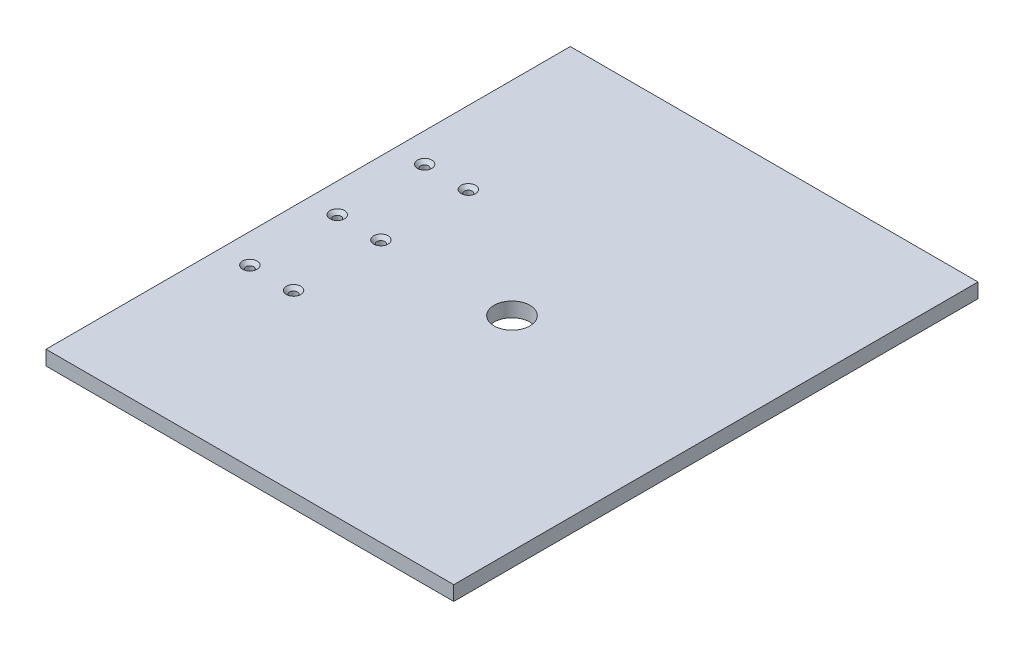
SolidWorks part; units mm, degrees
ref_plane "Front" through (0, 0, 0) normal (0, 0, 1) x (1, 0, 0)
ref_plane "Top" through (0, 0, 0) normal (0, 1, 0) x (1, 0, 0)
ref_plane "Right" through (0, 0, 0) normal (1, 0, 0) x (0, 0, -1)
sketch "Sketch1" plane through (0, 0, 0) normal (0, 1, 0) x (1, 0, 0)
  line L1 (0, -114.3) -> (177.8, -114.3)
  line L2 (0, -114.3) -> (0, 114.3)
  line L3 (0, 114.3) -> (177.8, 114.3)
  line L4 (177.8, -114.3) -> (177.8, 114.3)
  line L5 (0, -114.3) -> (177.8, 114.3) construction
  line L6 (0, 114.3) -> (177.8, -114.3) construction
  point P0 (88.9, 0)
  dimension "D1" = 177.8
  dimension "D2" = 228.6
extrude "Boss-Extrude1" add sketch "Sketch1" along normal blind 6.35
sketch "Sketch6" plane through (0, 6.35, 0) normal (0, 1, 0) x (1, 0, 0)
  line L0 (0, 0) -> (177.8, 0) construction
  line L1 (0, 114.3) -> (0, -114.3) construction
  line L2 (177.8, -114.3) -> (177.8, 114.3) construction
  circle A0 centre (88.9, 0) radius 7.81
  dimension "D1" = 15.62
  dimension "D2" = 88.9
extrude "Cut-Extrude1" cut sketch "Sketch6" against normal up to next
hole_wizard "Threaded CSK for M3-10 Flat Head Machine Screw1" positions "Sketch8" profile "Sketch7" countersink size "M3" standard "ANSI Metric" end condition through all
sketch "Sketch8" plane through (0, 6.35, 0) normal (0, -1, 0) x (-1, 0, 0)
  line L0 (-12.7, 114.3) -> (-12.7, -114.3) construction
  line L1 (-177.8, 114.3) -> (0, 114.3) construction
  line L2 (0, -114.3) -> (-177.8, -114.3) construction
  line L4 (0, 0) -> (-177.8, 0) construction
  line L5 (-177.8, -114.3) -> (-177.8, 114.3) construction
  line L7 (0, 114.3) -> (0, -114.3) construction
  line L8 (-31.75, -114.3) -> (-31.75, 114.3) construction
  line L9 (-177.8, 114.3) -> (0, 114.3) construction
  point P6 (-12.7, 0)
  point P29 (-12.7, -38.1)
  point P43 (-31.75, -38.1)
  point P45 (-12.7, 38.1)
  point P47 (-31.75, 38.1)
  point P52 (-31.75, 0)
  dimension "D1" = 12.7
  dimension "D2" = 19.05
  dimension "D3" = 38.1
  dimension "D4" = 38.1
sketch "Sketch7" plane through (12.7, 6.35, 0) normal (1, 0, 0) x (0, 0, 1)
  line L0 (0, 0) -> (0, 6.35)
  line L1 (0, 6.35) -> (1.7, 6.35)
  line L2 (1.7, 6.35) -> (1.7, 1.45)
  line L3 (1.7, 1.45) -> (3.15, 0)
  line L5 (3.15, 0) -> (0, 0)
  line L6 (-1.7, 1.45) -> (-3.15, 0) construction
  line L11 (0, -6.35) -> (0, 107.95) construction
  dimension "Thru Hole Dia." = 3.4
  dimension "Thru Hole Depth" = 6.35
  dimension "Near C'Sink Dia." = 6.3
  dimension "Near C'Sink Angle" = 90
